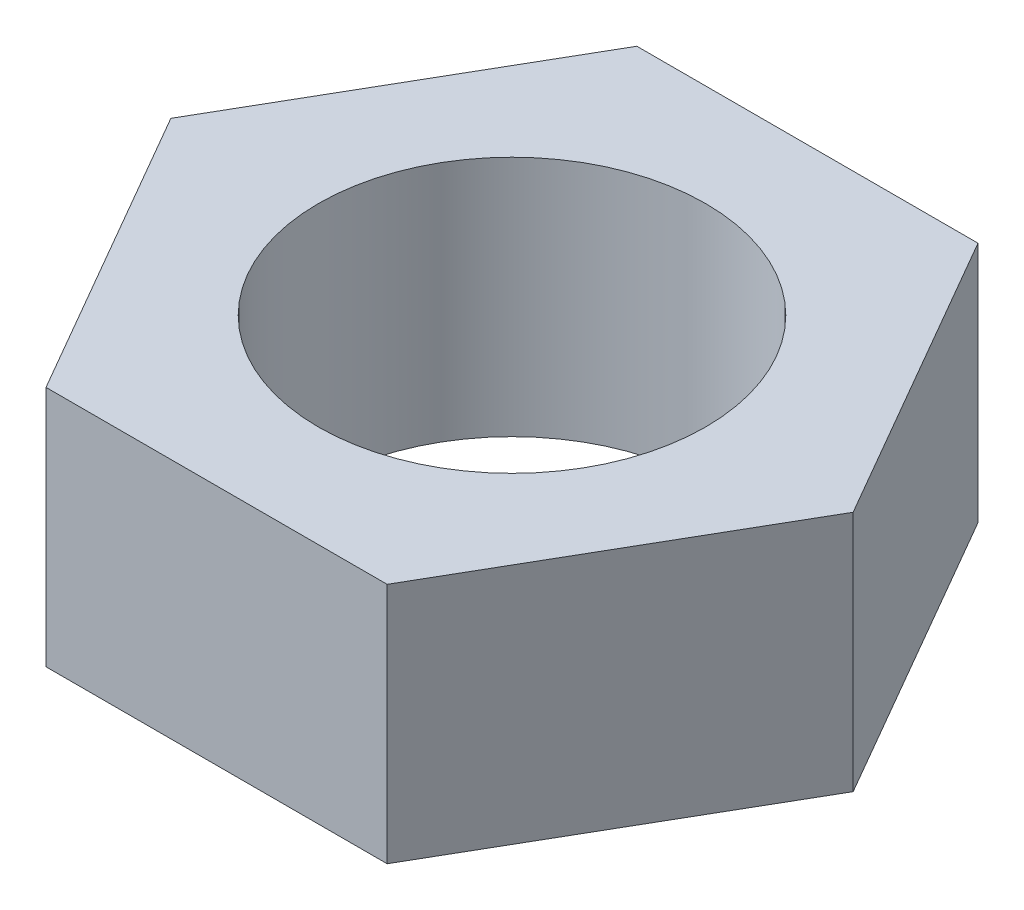
SolidWorks part; units mm, degrees
ref_plane "Alzado" through (0, 0, 0) normal (0, 0, 1) x (1, 0, 0)
ref_plane "Planta" through (0, 0, 0) normal (0, 1, 0) x (1, 0, 0)
ref_plane "Vista lateral" through (0, 0, 0) normal (1, 0, 0) x (0, 0, -1)
sketch "Croquis1" plane through (0, 0, 0) normal (0, 1, 0) x (1, 0, 0)
  line L1 (7.048, 0) -> (3.524, 6.1038)
  line L2 (3.524, 6.1038) -> (-3.524, 6.1038)
  line L3 (-3.524, 6.1038) -> (-7.048, 0)
  line L4 (-7.048, 0) -> (-3.524, -6.1038)
  line L5 (-3.524, -6.1038) -> (3.524, -6.1038)
  line L6 (3.524, -6.1038) -> (7.048, 0)
  circle A0 centre (0, 0) radius 6.1038 construction
  circle A1 centre (0, 0) radius 4
  dimension "D2" = 8
extrude "Saliente-Extruir1" add sketch "Croquis1" along normal blind 5
